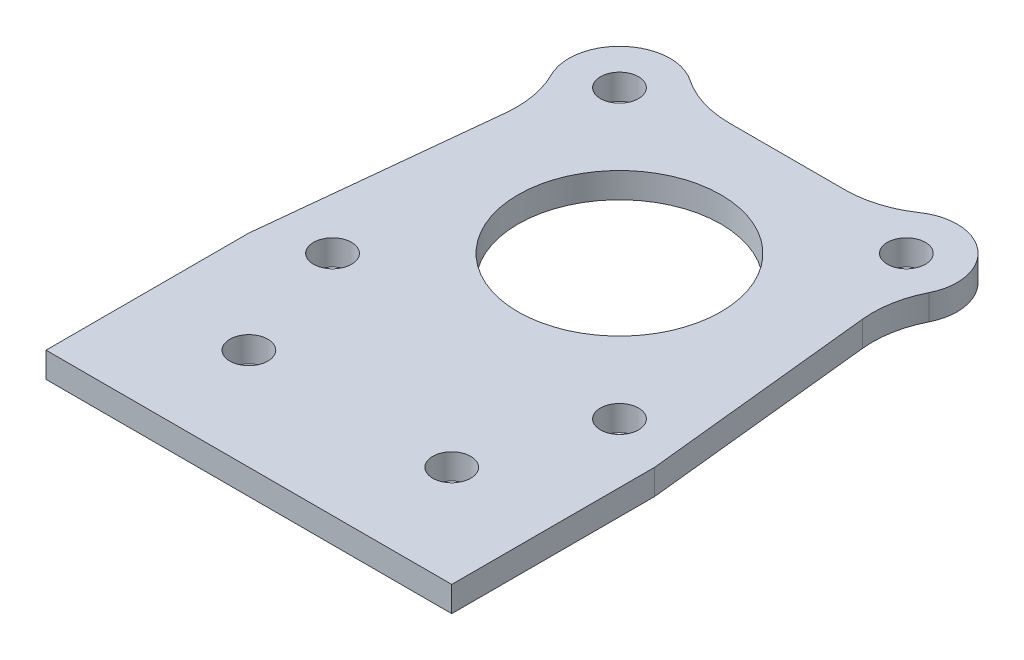
SolidWorks part; units mm, degrees
ref_plane "Front Plane" through (0, 0, 0) normal (0, 0, 1) x (1, 0, 0)
ref_plane "Top Plane" through (0, 0, 0) normal (0, 1, 0) x (1, 0, 0)
ref_plane "Right Plane" through (0, 0, 0) normal (1, 0, 0) x (0, 0, -1)
sketch "Sketch1" plane through (0, 0, 0) normal (0, 1, 0) x (1, 0, 0)
  line L0 (-21, 0) -> (-21, -25.4) construction
  line L3 (0, 42) -> (-42, 42)
  line L5 (-46.4, 0) -> (-42, 42)
  line L7 (4.4, 0) -> (4.4, -25.4)
  line L8 (4.4, -25.4) -> (-46.4, -25.4)
  line L9 (-46.4, 0) -> (-46.4, -25.4)
  line L10 (0, 42) -> (4.4, 0)
  point P11 (-21, -25.4)
  dimension "D1" = 42
  dimension "D3" = 25.4
  dimension "D4" = 50.8
extrude "Boss-Extrude1" add sketch "Sketch1" along normal blind 3.175
hole_wizard "1 (1) Diameter Hole1" positions "Sketch5" profile "Sketch4" hole size "1" standard "ANSI Inch" end condition through all
sketch "Sketch5" plane through (0, 3.175, 0) normal (0, 1, 0) x (1, 0, 0)
  line L3 (-21, 42) -> (-21, 0) construction
  line L4 (0, 42) -> (-42, 42) construction
  point P19 (-21, 21)
sketch "Sketch4" plane through (-21, 3.175, -21) normal (1, 0, 0) x (0, 0, 1)
  line L0 (0, 0) -> (0, 3.175)
  line L1 (0, 3.175) -> (12.7, 3.175)
  line L2 (12.7, 3.175) -> (12.7, 0)
  line L5 (12.7, 0) -> (0, 0)
  line L11 (0, -6.35) -> (0, 107.95) construction
  dimension "Thru Hole Dia." = 25.4
  dimension "Thru Hole Depth" = 3.175
sketch "Sketch6" plane through (0, 3.175, 0) normal (0, 1, 0) x (1, 0, 0)
  line L0 (-21, 21) -> (-21, 42) construction
  line L1 (0, 42) -> (-42, 42) construction
  line L2 (-3.5, 38.5) -> (-38.5, 38.5) construction
  line L3 (-33.7, 21) -> (-8.3, 21) construction
  line L4 (-21, 21) -> (-45.1077, 45.1077) construction
  circle A2 centre (-21, 21) radius 12.7 construction
  circle A5 centre (-38.9605, 38.9605) radius 2.3812
  circle A6 centre (-38.9605, 3.0395) radius 2.3813
  circle A7 centre (-3.0395, 3.0395) radius 2.3812
  circle A8 centre (-3.0395, 38.9605) radius 2.3812
  point P8 (-21, 38.5)
  point P30 (-21, 21)
  dimension "D3" = 45
  dimension "D4" = 25.4
  dimension "D2" = 17.5
  dimension "D5" = 4
extrude "Cut-Extrude1" cut sketch "Sketch6" against normal through all
sketch "Sketch7" plane through (0, 3.175, 0) normal (0, 1, 0) x (1, 0, 0)
  line L0 (-21, 42) -> (-21, -25.4) construction
  line L1 (0, 42) -> (-42, 42) construction
  line L2 (-46.4, -25.4) -> (4.4, -25.4) construction
  circle A0 centre (-38.9605, 38.9605) radius 6.35
  circle A1 centre (-38.9605, 38.9605) radius 2.3812
  circle A2 centre (-3.0395, 38.9605) radius 6.35
  circle A3 centre (-3.0395, 38.9605) radius 2.3812
extrude "Boss-Extrude2" add sketch "Sketch7" against normal up to surface (3.175 mm away) up to face at (-3.0395, 0, -36.5793)
hole_wizard "3/16 (0.1875) Diameter Hole1" positions "Sketch9" profile "Sketch8" hole size "3/16" standard "ANSI Inch" end condition through all
sketch "Sketch9" plane through (0, 3.175, 0) normal (0, 1, 0) x (1, 0, 0)
  line L0 (-46.4, -12.7) -> (4.4, -12.7) construction
  line L1 (-46.4, 0) -> (-46.4, -25.4) construction
  line L2 (4.4, -25.4) -> (4.4, 0) construction
  line L3 (-21, -25.4) -> (-21, 42) construction
  line L4 (-46.4, -25.4) -> (4.4, -25.4) construction
  line L5 (-8.6148, 42) -> (-33.3852, 42) construction
  point P13 (-33.7, -12.7)
  point P15 (-8.3, -12.7)
  dimension "D1" = 12.7
  dimension "D2" = 12.7
sketch "Sketch8" plane through (-33.7, 3.175, 12.7) normal (1, 0, 0) x (0, 0, 1)
  line L0 (0, 0) -> (0, 3.175)
  line L1 (0, 3.175) -> (2.3812, 3.175)
  line L2 (2.3812, 3.175) -> (2.3812, 0)
  line L5 (2.3812, 0) -> (0, 0)
  line L11 (0, -6.35) -> (0, 107.95) construction
  dimension "Thru Hole Dia." = 4.7625
  dimension "Thru Hole Depth" = 3.175
fillet "Fillet1" radius 12.7 4 edges at (0.8447, 1.5875, -33.937) (-8.6148, 1.5875, -42) (-33.3852, 1.5875, -42) (-42.8447, 1.5875, -33.937)
